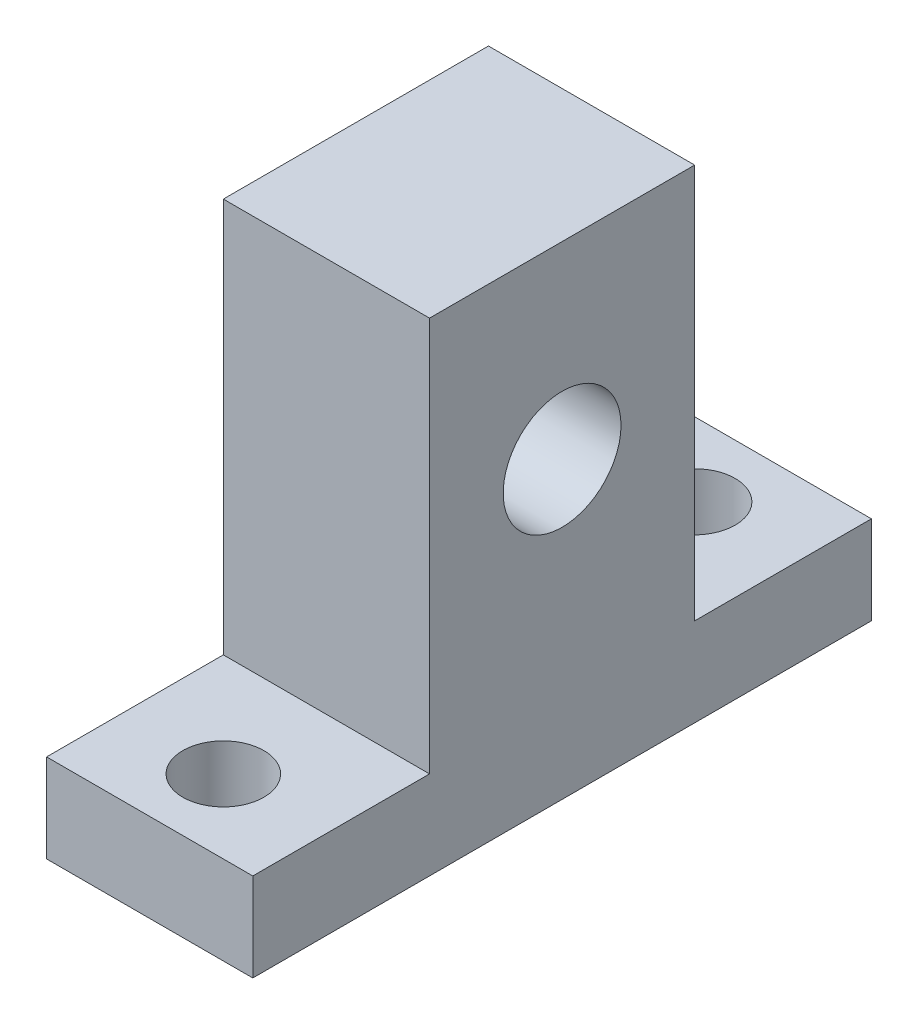
SolidWorks part; units mm, degrees
ref_plane "前视基准面" through (0, 0, 0) normal (0, 0, 1) x (1, 0, 0)
ref_plane "上视基准面" through (0, 0, 0) normal (0, 1, 0) x (1, 0, 0)
ref_plane "右视基准面" through (0, 0, 0) normal (1, 0, 0) x (0, 0, -1)
sketch "草图1" plane through (0, 0, 0) normal (1, 0, 0) x (0, 0, -1)
  line L0 (0, -544.5044) -> (0, 26680.7144) construction
  line L1 (21, 0) -> (-21, 0)
  line L2 (-21, 0) -> (-21, 6)
  line L3 (-21, 6) -> (-9, 6)
  line L4 (-9, 6) -> (-9, 32.8)
  line L5 (-9, 32.8) -> (9, 32.8)
  line L6 (9, 6) -> (9, 32.8)
  line L7 (21, 6) -> (9, 6)
  line L8 (21, 0) -> (21, 6)
  circle A0 centre (0, 20) radius 4
  point P12 (0, 32.8)
  point P15 (0, 0)
  dimension "D6" = 8
  dimension "D1" = 21
  dimension "D2" = 9
  dimension "D3" = 6
  dimension "D4" = 32.8
  dimension "D5" = 20
extrude "凸台-拉伸1" add sketch "草图1" along normal blind 14
sketch "草图2" plane through (0, 6, 0) normal (0, 1, 0) x (1, 0, 0)
  line L0 (7, 21) -> (7, -21) construction
  line L1 (14, 21) -> (0, 21) construction
  line L2 (14, -21) -> (0, -21) construction
  circle A0 centre (7, 16) radius 2.75
  circle A1 centre (7, -16) radius 2.75
  dimension "D1" = 16
  dimension "D3" = 5.5
  dimension "D4" = 5.5
  dimension "D2" = 16
extrude "切除-拉伸1" cut sketch "草图2" against normal blind 14
